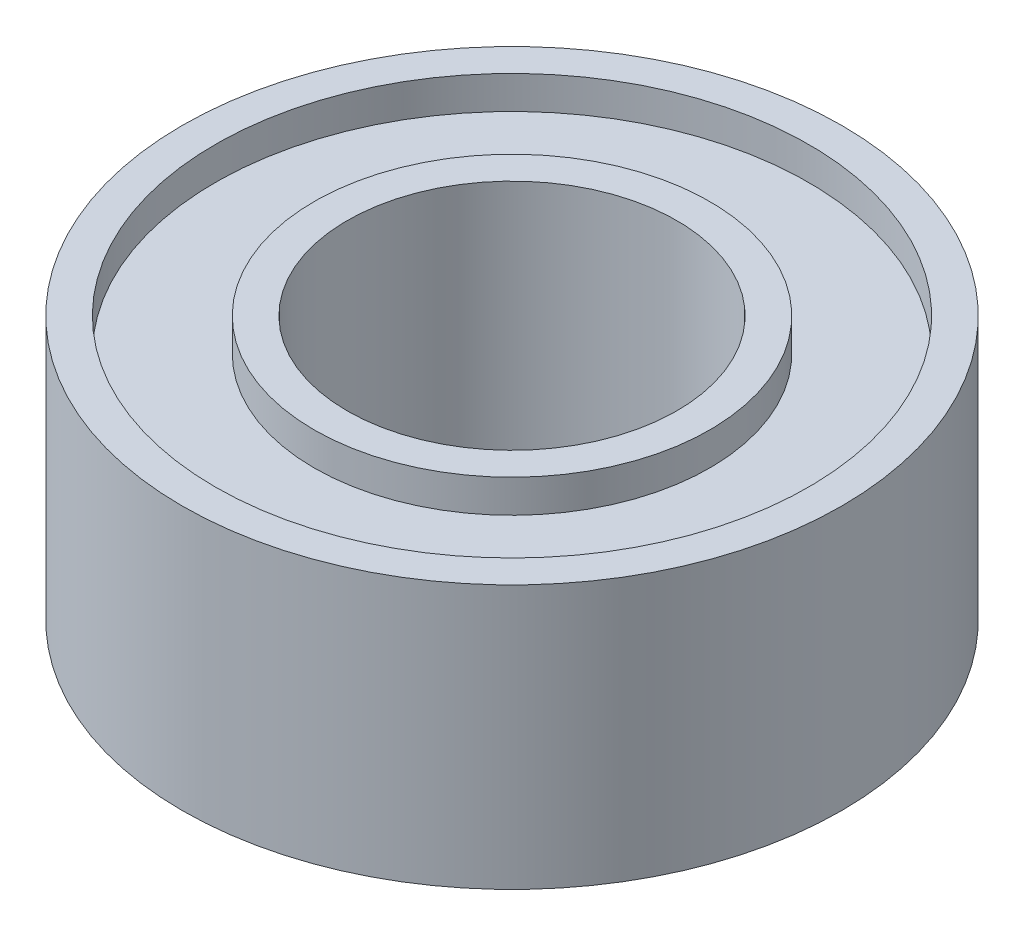
SolidWorks part; units mm, degrees
ref_plane "Front Plane" through (0, 0, 0) normal (0, 0, 1) x (1, 0, 0)
ref_plane "Top Plane" through (0, 0, 0) normal (0, 1, 0) x (1, 0, 0)
ref_plane "Right Plane" through (0, 0, 0) normal (1, 0, 0) x (0, 0, -1)
sketch "Sketch1" plane through (0, 0, 0) normal (0, 1, 0) x (1, 0, 0)
  circle A0 centre (0, 0) radius 2.5
  circle A1 centre (0, 0) radius 5
  dimension "D1" = 5
  dimension "D2" = 10
extrude "Boss-Extrude1" add sketch "Sketch1" along normal blind 4
sketch "Sketch2" plane through (0, 4, 0) normal (0, 1, 0) x (1, 0, 0)
  circle A0 centre (0, 0) radius 3
  circle A1 centre (0, 0) radius 4.5
  dimension "D1" = 6
  dimension "D2" = 9
extrude "Cut-Extrude1" cut sketch "Sketch2" against normal blind 0.5
sketch "Sketch3" plane through (0, 0, 0) normal (0, -1, 0) x (1, 0, 0)
  circle A0 centre (0, 0) radius 3
  circle A1 centre (0, 0) radius 4.5
  dimension "D1" = 6
  dimension "D2" = 9
extrude "Cut-Extrude2" cut sketch "Sketch3" against normal blind 0.5
